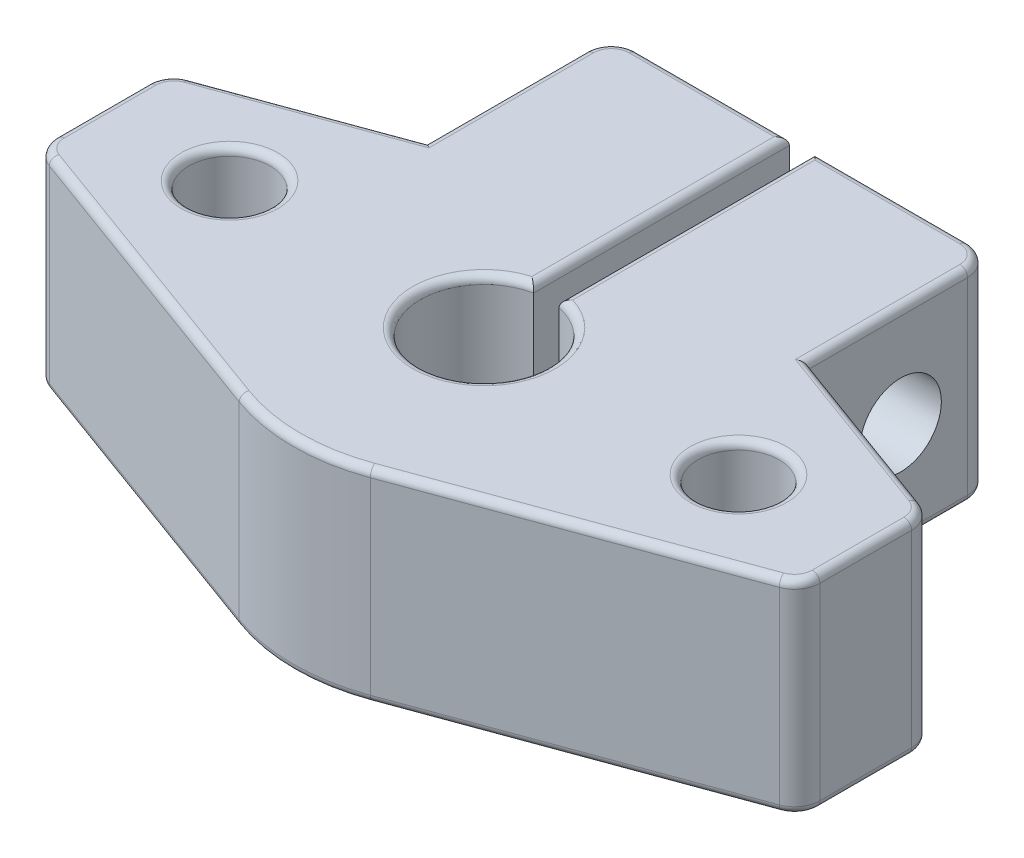
SolidWorks part; units mm, degrees
other "Kamera1"
ref_plane "Frontal" through (0, 0, 0) normal (0, 0, 1) x (1, 0, 0)
ref_plane "Planta" through (0, 0, 0) normal (0, 1, 0) x (1, 0, 0)
ref_plane "Lateral" through (0, 0, 0) normal (1, 0, 0) x (0, 0, -1)
sketch "Croquis 1" plane through (0, 0, 0) normal (0, 1, 0) x (1, 0, 0)
  line L0 (0, 9.8473) -> (0, 0) construction
  line L1 (-15, 2.5) -> (-15, -2.5)
  line L2 (15, 2.5) -> (15, -2.5)
  line L3 (-26.3879, 0) -> (27.7491, 0) construction
  line L4 (-10, 9.8473) -> (-10, -13.603) construction
  line L5 (10, 9.8473) -> (10, -13.603) construction
  line L6 (-15, 2.5) -> (-7.5, 5.2429)
  line L7 (-15, -2.5) -> (-2.576, -7.0437)
  line L8 (15, -2.5) -> (2.576, -7.0437)
  line L9 (15, 2.5) -> (7.5, 5.2429)
  line L10 (-0.5, 9.9875) -> (-0.5, 2.4495)
  line L11 (15, 9.8473) -> (15, -13.603) construction
  line L12 (-15, 9.8473) -> (-15, -13.603) construction
  line L13 (0.5, 9.9875) -> (0.5, 2.4495)
  line L14 (0.5, 9.8473) -> (0.5, -13.603) construction
  line L15 (-0.5, 9.8473) -> (-0.5, -13.603) construction
  line L16 (-0.5, 9.9875) -> (-0.5, 12.5)
  line L17 (-0.5, 12.5) -> (-7.5, 12.5)
  line L18 (0, 9.8473) -> (0, -13.603) construction
  line L19 (-7.5, 12.5) -> (-7.5, 5.2429)
  line L20 (0, 0) -> (0, -7.5) construction
  line L21 (7.5, 12.5) -> (7.5, 5.2429)
  line L22 (0.5, 12.5) -> (7.5, 12.5)
  line L23 (0.5, 9.9875) -> (0.5, 12.5)
  arc A0 (-0.5, 2.4495) -> (0.5, 2.4495) centre (0, 0) ccw
  arc A1 (-2.576, -7.0437) -> (2.576, -7.0437) centre (0, 0) ccw
  circle A2 centre (-10, 0) radius 1.6
  circle A3 centre (10, 0) radius 1.6
  dimension "D1" = 5
  dimension "D4" = 15
  dimension "D7" = 3.2
  dimension "D8" = 3.2
  dimension "D6" = 20
  dimension "D9" = 5
  dimension "D10" = 2.5
  dimension "D11" = 7
  dimension "D12" = 10
  dimension "D2" = 0.5
  dimension "D3" = 15
  dimension "D5" = 10
extrude "Saliente-Extruir1" add sketch "Croquis 1" along normal blind 8
fillet "Redondeo1" radius 1 1 edges at (15, 4, 2.5)
fillet "Redondeo2" radius 1 3 edges at (-15, 4, -2.5) (-15, 4, 2.5) (15, 4, -2.5)
sketch "Croquis 2" plane through (7.5, 0, 0) normal (1, 0, 0) x (0, 0, -1)
  line L0 (8.8715, 0) -> (8.8715, 8) construction
  line L1 (5.2429, 0) -> (12.5, 0) construction
  line L2 (5.2429, 8) -> (12.5, 8) construction
  circle A0 centre (8.8715, 4) radius 1.6
  dimension "D1" = 3.2
extrude "Corte-Extruir1" cut sketch "Croquis 2" against normal through all
fillet "Redondeo3" radius 1 2 edges at (7.5, 4, -12.5) (-7.5, 4, -12.5)
fillet "Redondeo4" radius 0.3 44 edges at (-3.5, 0, -12.5) (-7.2071, 0, -12.2071) (-7.5, 0, -8.3715) (-10.9217, 0, -3.9915) (-14.8196, 0, -2.3739) (-15, 0, 0) (-14.8196, 0, 2.3739) (-8.4598, 0, 4.8919) (0, 0, 7.5) (8.4598, 0, 4.8919) (14.8196, 0, 2.3739) (15, 0, 0) (14.8196, 0, -2.3739) (10.9217, 0, -3.9915) (7.5, 0, -8.3715) (7.2071, 0, -12.2071) (3.5, 0, -12.5) (0.5, 0, -7.4747) (-0.5, 0, -7.4747) (-0.5, 8, -7.4747) (0, 8, 7.5) (-8.4598, 8, 4.8919) (-14.8196, 8, 2.3739) (-15, 8, 0) (-14.8196, 8, -2.3739) (-10.9217, 8, -3.9915) (-7.5, 8, -8.3715) (-7.2071, 8, -12.2071) (-3.5, 8, -12.5) (10.9217, 8, -3.9915) (14.8196, 8, -2.3739) (15, 8, 0) (14.8196, 8, 2.3739) (8.4598, 8, 4.8919) (0.5, 8, -7.4747) (3.5, 8, -12.5) (7.2071, 8, -12.2071) (7.5, 8, -8.3715) (10, 0, 1.6) (-10, 0, 1.6) (0, 0, 2.5) (10, 8, 1.6) (0, 8, 2.5) (-10, 8, 1.6)
